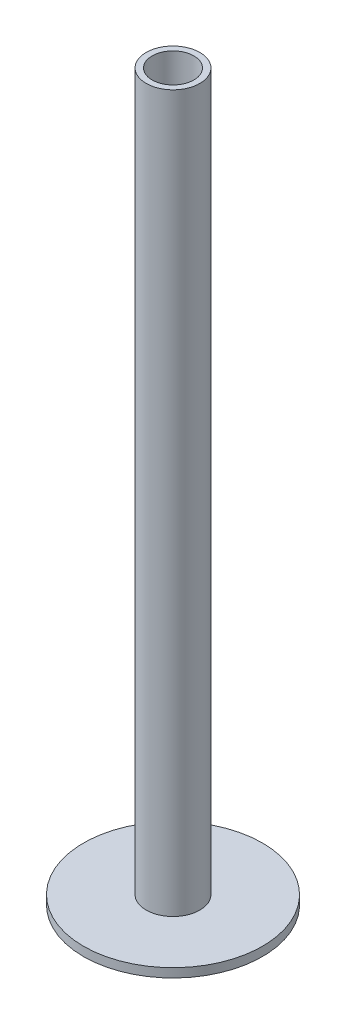
SolidWorks part; units mm, degrees
ref_plane "Front Plane" through (0, 0, 0) normal (0, 0, 1) x (1, 0, 0)
ref_plane "Top Plane" through (0, 0, 0) normal (0, 1, 0) x (1, 0, 0)
ref_plane "Right Plane" through (0, 0, 0) normal (1, 0, 0) x (0, 0, -1)
sketch "Sketch1" plane through (0, 0, 0) normal (0, 1, 0) x (1, 0, 0)
  circle A0 centre (0, 0) radius 9
  circle A1 centre (0, 0) radius 7
  dimension "D1" = 18
  dimension "D2" = 14
extrude "Boss-Extrude1" add sketch "Sketch1" along normal blind 240 contours A0 A1
sketch "Sketch2" plane through (0, 0, 0) normal (0, -1, 0) x (1, 0, 0)
  circle A0 centre (0, 0) radius 30
  circle A1 centre (0, 0) radius 7 construction
  circle A2 centre (0, 0) radius 7
  dimension "D1" = 60
extrude "Boss-Extrude2" add sketch "Sketch2" along normal blind 3 contours A0 | A2
